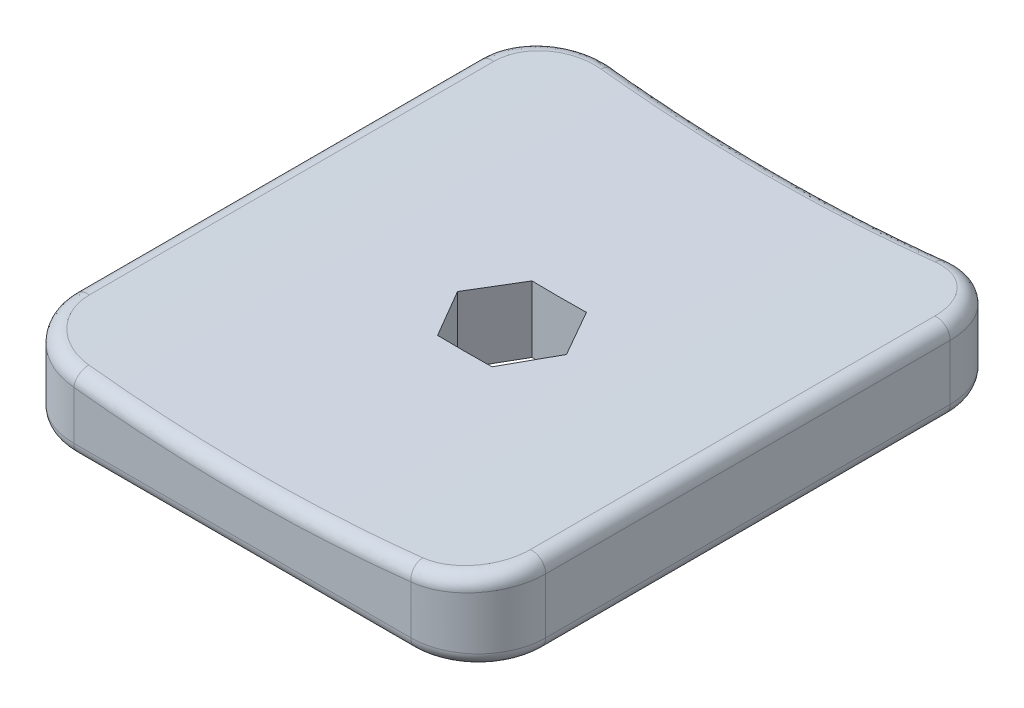
SolidWorks part; units mm, degrees
material "ABS"
ref_plane "Front Plane" through (0, 0, 0) normal (0, 0, 1) x (1, 0, 0)
ref_plane "Top Plane" through (0, 0, 0) normal (0, 1, 0) x (1, 0, 0)
ref_plane "Right Plane" through (0, 0, 0) normal (1, 0, 0) x (0, 0, -1)
sketch "Sketch1" plane through (0, 0, 0) normal (0, 1, 0) x (1, 0, 0)
  line L1 (12.5, -20) -> (-12.5, -20)
  line L2 (17.5, -15) -> (17.5, 15)
  line L3 (12.5, 20) -> (-12.5, 20)
  line L4 (-17.5, -15) -> (-17.5, 15)
  line L5 (17.5, -20) -> (-17.5, 20) construction
  line L6 (17.5, 20) -> (-17.5, -20) construction
  line L7 (4.0415, 0) -> (2.0207, 3.5)
  line L8 (2.0207, 3.5) -> (-2.0207, 3.5)
  line L9 (-2.0207, 3.5) -> (-4.0415, 0)
  line L10 (-4.0415, 0) -> (-2.0207, -3.5)
  line L11 (-2.0207, -3.5) -> (2.0207, -3.5)
  line L12 (2.0207, -3.5) -> (4.0415, 0)
  circle A0 centre (0, 0) radius 3.5 construction
  arc A1 (12.5, 20) -> (17.5, 15) centre (12.5, 15) cw
  arc A2 (12.5, -20) -> (17.5, -15) centre (12.5, -15) ccw
  arc A3 (-12.5, -20) -> (-17.5, -15) centre (-12.5, -15) cw
  arc A4 (-17.5, 15) -> (-12.5, 20) centre (-12.5, 15) cw
  point P0 (0, 0)
  dimension "D3" = 20
  dimension "D1" = 7
  dimension "D4" = 5
  dimension "D2" = 17.5
extrude "Boss-Extrude1" add sketch "Sketch1" against normal blind 6.27
sketch "Sketch2" plane through (0, 0, 20) normal (0, 0, 1) x (1, 0, 0)
  line L0 (17.5, 0) -> (-17.5, 0)
  line L2 (-12.5, -6.27) -> (-12.5, 0) construction
  line L3 (-12.5, 0) -> (12.5, 0) construction
  spline S0 degree 2 poles (-17.5, 0) (0, -2.74) (17.5, 0) knots 0 0 0 1 1 1
  dimension "D1" = 12.5
  dimension "D2" = 1.37
extrude "Cut-Extrude1" cut sketch "Sketch2" against normal through all
fillet "Fillet1" radius 1 16 edges at (-16.0355, -6.27, 18.5355) (-17.5, -6.27, 0) (-16.0355, -6.27, -18.5355) (0, -6.27, -20) (16.0355, -6.27, -18.5355) (17.5, -6.27, 0) (16.0355, -6.27, 18.5355) (-16.4252, -0.1631, 18.0972) (-17.5, 0, 0) (-15.6411, -0.2756, -18.8902) (16.4252, -0.1631, -18.0972) (17.5, 0, 0) (15.6411, -0.2756, 18.8902) (0, -6.27, 20)
sketch "Sketch3" plane through (0, -6.27, 0) normal (0, -1, 0) x (1, 0, 0)
  circle A0 centre (0, 0) radius 7.0821
